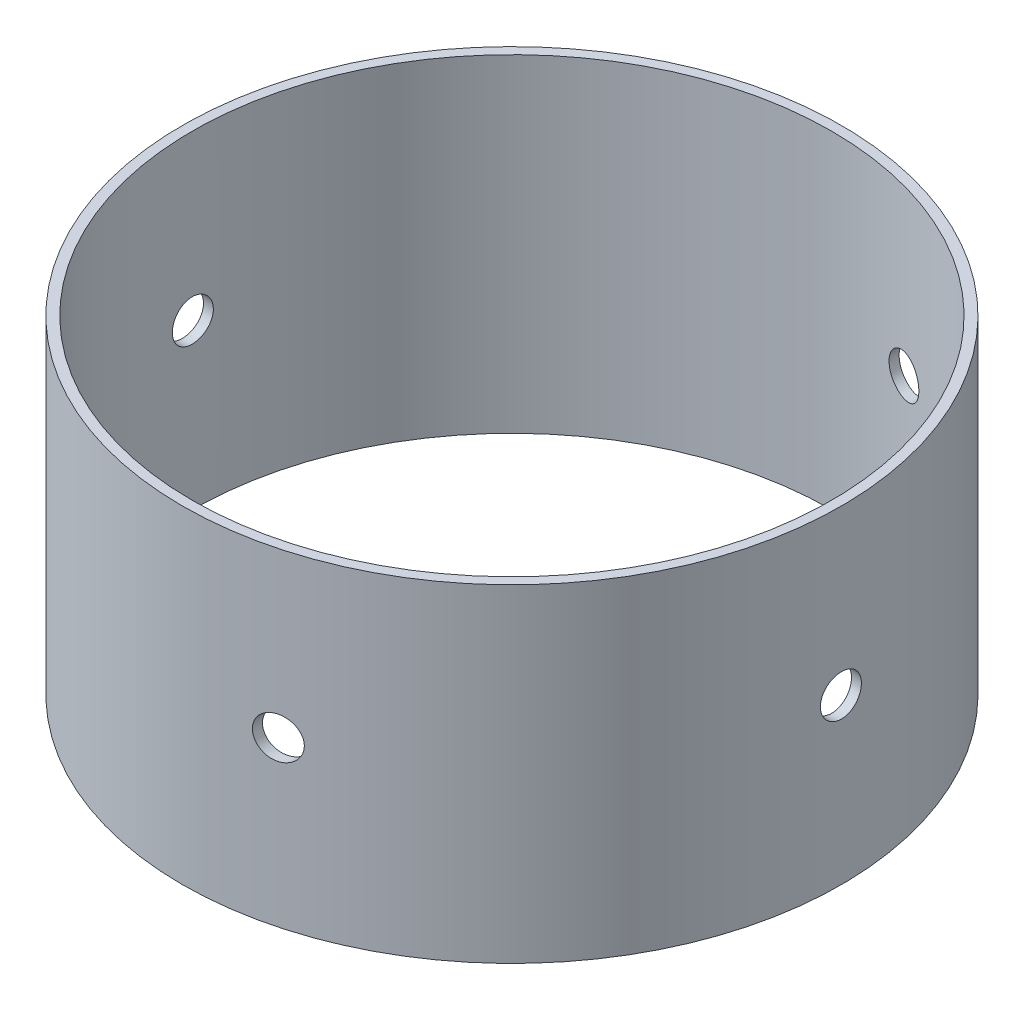
SolidWorks part; units mm, degrees
material "Custom Plastic"
ref_plane "Front Plane" through (0, 0, 0) normal (0, 0, 1) x (1, 0, 0)
ref_plane "Top Plane" through (0, 0, 0) normal (0, 1, 0) x (1, 0, 0)
ref_plane "Right Plane" through (0, 0, 0) normal (1, 0, 0) x (0, 0, -1)
sketch "Sketch1" plane through (0, 0, 0) normal (0, 1, 0) x (1, 0, 0)
  circle A0 centre (0, 0) radius 51.054
  circle A1 centre (0, 0) radius 49.53
  dimension "D1" = 99.06
  dimension "D2" = 102.108
extrude "Boss-Extrude1" add sketch "Sketch1" along normal blind 50.8
sketch "Sketch2" plane through (0, 0, 0) normal (0, 0, 1) x (1, 0, 0)
  line L0 (0, 53.2648) -> (0, -12.008) construction
  line L1 (-52.4984, 25.4) -> (57.7951, 25.4) construction
  circle A0 centre (13.0658, 25.4) radius 3.175
  dimension "D2" = 6.35
  dimension "D1" = 13.0658
extrude "Cut-Extrude1" cut sketch "Sketch2" against normal through all both and the other way through all
sketch "Sketch3" plane through (0, 0, 0) normal (1, 0, 0) x (0, 0, -1)
  line L0 (0, 50.8) -> (0, -10.6967) construction
  line L1 (49.53, 50.8) -> (-49.53, 50.8) construction
  line L2 (51.054, 25.4) -> (-73.0676, 25.4) construction
  line L3 (51.054, 0) -> (51.054, 50.8) construction
  circle A0 centre (0, 25.4) radius 3.175
  dimension "D2" = 6.35
  dimension "D1" = 51.054
extrude "Cut-Extrude2" cut sketch "Sketch3" against normal through all both and the other way through all
